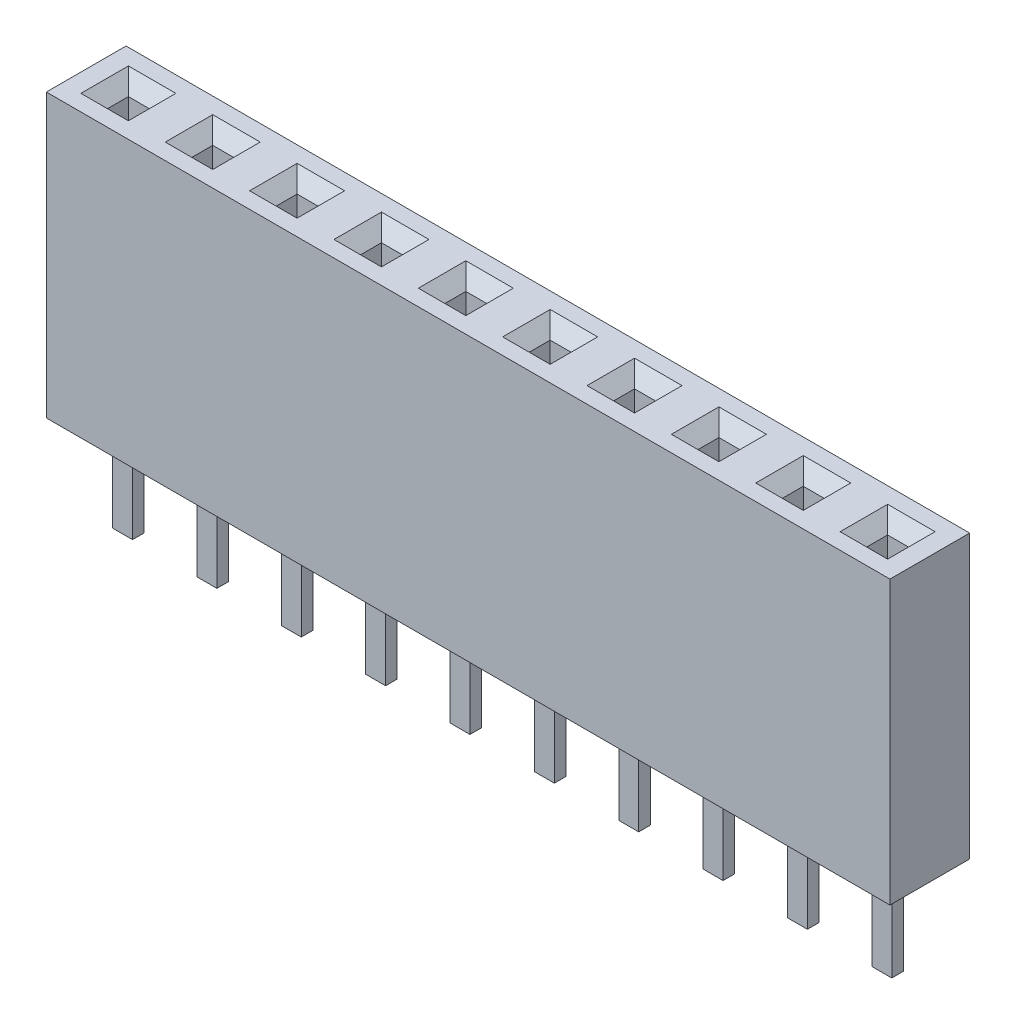
SolidWorks part; units mm, degrees
ref_plane "Front Plane" through (0, 0, 0) normal (0, 0, 1) x (1, 0, 0)
ref_plane "Top Plane" through (0, 0, 0) normal (0, 1, 0) x (1, 0, 0)
ref_plane "Right Plane" through (0, 0, 0) normal (1, 0, 0) x (0, 0, -1)
sketch "Sketch1" plane through (0, 0, 0) normal (0, 1, 0) x (1, 0, 0)
  line L1 (19.05, -1.2) -> (-19.05, -1.2)
  line L2 (19.05, -1.2) -> (19.05, 1.2)
  line L3 (19.05, 1.2) -> (-19.05, 1.2)
  line L4 (-19.05, -1.2) -> (-19.05, 1.2)
  line L5 (19.05, -1.2) -> (-19.05, 1.2) construction
  line L6 (19.05, 1.2) -> (-19.05, -1.2) construction
  point P0 (0, 0)
  dimension "D1" = 2.4
  dimension "D2" = 38.1
extrude "Boss-Extrude1" add sketch "Sketch1" along normal blind 8.5
sketch "Sketch2" plane through (0, 8.5, 0) normal (0, 1, 0) x (1, 0, 0)
  line L0 (-19.05, 0) -> (19.05, 0) construction
  line L1 (-19.05, 1.2) -> (-19.05, -1.2) construction
  line L2 (19.05, -1.2) -> (19.05, 1.2) construction
  line L3 (-15.555, 0.315) -> (-14.925, 0.315)
  line L4 (-18.095, -0.315) -> (-17.465, -0.315)
  line L5 (-18.095, -0.315) -> (-18.095, 0.315)
  line L6 (-18.095, 0.315) -> (-17.465, 0.315)
  line L7 (-17.465, -0.315) -> (-17.465, 0.315)
  line L8 (-18.095, -0.315) -> (-17.465, 0.315) construction
  line L9 (-18.095, 0.315) -> (-17.465, -0.315) construction
  line L10 (-15.555, -0.315) -> (-15.555, 0.315)
  line L11 (-15.555, -0.315) -> (-14.925, -0.315)
  line L12 (-14.925, -0.315) -> (-14.925, 0.315)
  line L13 (-13.015, 0.315) -> (-12.385, 0.315)
  line L14 (-13.015, -0.315) -> (-13.015, 0.315)
  line L15 (-13.015, -0.315) -> (-12.385, -0.315)
  line L16 (-12.385, -0.315) -> (-12.385, 0.315)
  line L17 (-10.475, 0.315) -> (-9.845, 0.315)
  line L18 (-10.475, -0.315) -> (-10.475, 0.315)
  line L19 (-10.475, -0.315) -> (-9.845, -0.315)
  line L20 (-9.845, -0.315) -> (-9.845, 0.315)
  line L21 (-7.935, 0.315) -> (-7.305, 0.315)
  line L22 (-7.935, -0.315) -> (-7.935, 0.315)
  line L23 (-7.935, -0.315) -> (-7.305, -0.315)
  line L24 (-7.305, -0.315) -> (-7.305, 0.315)
  line L25 (-5.395, 0.315) -> (-4.765, 0.315)
  line L26 (-5.395, -0.315) -> (-5.395, 0.315)
  line L27 (-5.395, -0.315) -> (-4.765, -0.315)
  line L28 (-4.765, -0.315) -> (-4.765, 0.315)
  line L29 (-2.855, 0.315) -> (-2.225, 0.315)
  line L30 (-2.855, -0.315) -> (-2.855, 0.315)
  line L31 (-2.855, -0.315) -> (-2.225, -0.315)
  line L32 (-2.225, -0.315) -> (-2.225, 0.315)
  line L33 (-0.315, 0.315) -> (0.315, 0.315)
  line L34 (-0.315, -0.315) -> (-0.315, 0.315)
  line L35 (-0.315, -0.315) -> (0.315, -0.315)
  line L36 (0.315, -0.315) -> (0.315, 0.315)
  line L37 (2.225, 0.315) -> (2.855, 0.315)
  line L38 (2.225, -0.315) -> (2.225, 0.315)
  line L39 (2.225, -0.315) -> (2.855, -0.315)
  line L40 (2.855, -0.315) -> (2.855, 0.315)
  line L41 (4.765, 0.315) -> (5.395, 0.315)
  line L42 (4.765, -0.315) -> (4.765, 0.315)
  line L43 (4.765, -0.315) -> (5.395, -0.315)
  line L44 (5.395, -0.315) -> (5.395, 0.315)
  line L45 (7.305, 0.315) -> (7.935, 0.315)
  line L46 (7.305, -0.315) -> (7.305, 0.315)
  line L47 (7.305, -0.315) -> (7.935, -0.315)
  line L48 (7.935, -0.315) -> (7.935, 0.315)
  line L49 (9.845, 0.315) -> (10.475, 0.315)
  line L50 (9.845, -0.315) -> (9.845, 0.315)
  line L51 (9.845, -0.315) -> (10.475, -0.315)
  line L52 (10.475, -0.315) -> (10.475, 0.315)
  line L53 (12.385, 0.315) -> (13.015, 0.315)
  line L54 (12.385, -0.315) -> (12.385, 0.315)
  line L55 (12.385, -0.315) -> (13.015, -0.315)
  line L56 (13.015, -0.315) -> (13.015, 0.315)
  line L57 (14.925, 0.315) -> (15.555, 0.315)
  line L58 (14.925, -0.315) -> (14.925, 0.315)
  line L59 (14.925, -0.315) -> (15.555, -0.315)
  line L60 (15.555, -0.315) -> (15.555, 0.315)
  line L61 (17.465, 0.315) -> (18.095, 0.315)
  line L62 (17.465, -0.315) -> (17.465, 0.315)
  line L63 (17.465, -0.315) -> (18.095, -0.315)
  line L64 (18.095, -0.315) -> (18.095, 0.315)
  point P6 (-17.78, 0)
  dimension "D1" = 0.63
  dimension "D2" = 0.63
  dimension "D3" = 1.27
  dimension "D4" = 15
extrude "Cut-Extrude1" cut sketch "Sketch2" against normal blind 6.5
sketch "Sketch3" plane through (0, 0, 0) normal (0, -1, 0) x (1, 0, 0)
  line L0 (-19.05, 0) -> (19.05, 0) construction
  line L1 (-19.05, -1.2) -> (-19.05, 1.2) construction
  line L2 (19.05, 1.2) -> (19.05, -1.2) construction
  line L3 (-15.54, 0.175) -> (-14.94, 0.175)
  line L4 (-18.08, -0.175) -> (-17.48, -0.175)
  line L5 (-18.08, -0.175) -> (-18.08, 0.175)
  line L6 (-18.08, 0.175) -> (-17.48, 0.175)
  line L7 (-17.48, -0.175) -> (-17.48, 0.175)
  line L8 (-18.08, -0.175) -> (-17.48, 0.175) construction
  line L9 (-18.08, 0.175) -> (-17.48, -0.175) construction
  line L10 (-15.54, -0.175) -> (-15.54, 0.175)
  line L11 (-15.54, -0.175) -> (-14.94, -0.175)
  line L12 (-14.94, -0.175) -> (-14.94, 0.175)
  line L13 (-13, 0.175) -> (-12.4, 0.175)
  line L14 (-13, -0.175) -> (-13, 0.175)
  line L15 (-13, -0.175) -> (-12.4, -0.175)
  line L16 (-12.4, -0.175) -> (-12.4, 0.175)
  line L17 (-10.46, 0.175) -> (-9.86, 0.175)
  line L18 (-10.46, -0.175) -> (-10.46, 0.175)
  line L19 (-10.46, -0.175) -> (-9.86, -0.175)
  line L20 (-9.86, -0.175) -> (-9.86, 0.175)
  line L21 (-7.92, 0.175) -> (-7.32, 0.175)
  line L22 (-7.92, -0.175) -> (-7.92, 0.175)
  line L23 (-7.92, -0.175) -> (-7.32, -0.175)
  line L24 (-7.32, -0.175) -> (-7.32, 0.175)
  line L25 (-5.38, 0.175) -> (-4.78, 0.175)
  line L26 (-5.38, -0.175) -> (-5.38, 0.175)
  line L27 (-5.38, -0.175) -> (-4.78, -0.175)
  line L28 (-4.78, -0.175) -> (-4.78, 0.175)
  line L29 (-2.84, 0.175) -> (-2.24, 0.175)
  line L30 (-2.84, -0.175) -> (-2.84, 0.175)
  line L31 (-2.84, -0.175) -> (-2.24, -0.175)
  line L32 (-2.24, -0.175) -> (-2.24, 0.175)
  line L33 (-0.3, 0.175) -> (0.3, 0.175)
  line L34 (-0.3, -0.175) -> (-0.3, 0.175)
  line L35 (-0.3, -0.175) -> (0.3, -0.175)
  line L36 (0.3, -0.175) -> (0.3, 0.175)
  line L37 (2.24, 0.175) -> (2.84, 0.175)
  line L38 (2.24, -0.175) -> (2.24, 0.175)
  line L39 (2.24, -0.175) -> (2.84, -0.175)
  line L40 (2.84, -0.175) -> (2.84, 0.175)
  line L41 (4.78, 0.175) -> (5.38, 0.175)
  line L42 (4.78, -0.175) -> (4.78, 0.175)
  line L43 (4.78, -0.175) -> (5.38, -0.175)
  line L44 (5.38, -0.175) -> (5.38, 0.175)
  line L45 (7.32, 0.175) -> (7.92, 0.175)
  line L46 (7.32, -0.175) -> (7.32, 0.175)
  line L47 (7.32, -0.175) -> (7.92, -0.175)
  line L48 (7.92, -0.175) -> (7.92, 0.175)
  line L49 (9.86, 0.175) -> (10.46, 0.175)
  line L50 (9.86, -0.175) -> (9.86, 0.175)
  line L51 (9.86, -0.175) -> (10.46, -0.175)
  line L52 (10.46, -0.175) -> (10.46, 0.175)
  line L53 (12.4, 0.175) -> (13, 0.175)
  line L54 (12.4, -0.175) -> (12.4, 0.175)
  line L55 (12.4, -0.175) -> (13, -0.175)
  line L56 (13, -0.175) -> (13, 0.175)
  line L57 (14.94, 0.175) -> (15.54, 0.175)
  line L58 (14.94, -0.175) -> (14.94, 0.175)
  line L59 (14.94, -0.175) -> (15.54, -0.175)
  line L60 (15.54, -0.175) -> (15.54, 0.175)
  line L61 (17.48, 0.175) -> (18.08, 0.175)
  line L62 (17.48, -0.175) -> (17.48, 0.175)
  line L63 (17.48, -0.175) -> (18.08, -0.175)
  line L64 (18.08, -0.175) -> (18.08, 0.175)
  point P6 (-17.78, 0)
  dimension "D1" = 0.35
  dimension "D2" = 0.6
  dimension "D3" = 1.27
  dimension "D4" = 15
extrude "Boss-Extrude2" add sketch "Sketch3" along normal blind 2.9
chamfer "Chamfer1" distance 0.4 angle 45 60 edges at (0, 8.5, 0.315) (0.315, 8.5, 0) (0, 8.5, -0.315) (-0.315, 8.5, 0) (-2.54, 8.5, 0.315) (-2.225, 8.5, 0) (-2.54, 8.5, -0.315) (-2.855, 8.5, 0) (-5.08, 8.5, 0.315) (-4.765, 8.5, 0) (-5.08, 8.5, -0.315) (-5.395, 8.5, 0) (-7.62, 8.5, 0.315) (-7.305, 8.5, 0) (-7.62, 8.5, -0.315) (-7.935, 8.5, 0) (-10.16, 8.5, 0.315) (-9.845, 8.5, 0) (-10.16, 8.5, -0.315) (-10.475, 8.5, 0) (-12.385, 8.5, 0) (-12.7, 8.5, -0.315) (-13.015, 8.5, 0) (-12.7, 8.5, 0.315) (-15.24, 8.5, 0.315) (-14.925, 8.5, 0) (-15.24, 8.5, -0.315) (-15.555, 8.5, 0) (-17.78, 8.5, 0.315) (-17.465, 8.5, 0) (-17.78, 8.5, -0.315) (-18.095, 8.5, 0) (17.78, 8.5, 0.315) (18.095, 8.5, 0) (17.78, 8.5, -0.315) (17.465, 8.5, 0) (15.24, 8.5, 0.315) (15.555, 8.5, 0) (15.24, 8.5, -0.315) (14.925, 8.5, 0) (12.385, 8.5, 0) (12.7, 8.5, 0.315) (13.015, 8.5, 0) (12.7, 8.5, -0.315) (9.845, 8.5, 0) (10.16, 8.5, 0.315) (10.475, 8.5, 0) (10.16, 8.5, -0.315) (7.305, 8.5, 0) (7.62, 8.5, 0.315) (7.935, 8.5, 0) (7.62, 8.5, -0.315) (4.765, 8.5, 0) (5.08, 8.5, 0.315) (5.395, 8.5, 0) (5.08, 8.5, -0.315) (2.225, 8.5, 0) (2.54, 8.5, -0.315) (2.855, 8.5, 0) (2.54, 8.5, 0.315)
sketch "Sketch4" plane through (0, 8.5, 0) normal (0, 1, 0) x (1, 0, 0)
  line L0 (5.395, 0) -> (7.305, 0) construction
  line L3 (6.35, 0) -> (6.35, 2.1388) construction
  line L4 (5.395, -0.315) -> (5.395, 0.315) construction
  line L5 (6.35, 2.1388) -> (25.7288, 2.1388)
  line L6 (6.35, 2.1388) -> (6.35, -2.3327)
  line L7 (6.35, -2.3327) -> (25.7288, -2.3327)
  line L8 (25.7288, 2.1388) -> (25.7288, -2.3327)
  line L9 (7.305, 0.315) -> (7.305, -0.315) construction
  point P11 (6.35, 0)
extrude "Cut-Extrude2" cut sketch "Sketch4" against normal through all
sketch "Sketch5" plane through (0, 0, 0) normal (0, -1, 0) x (-1, 0, 0)
  line L0 (17.78, -1.2) -> (17.78, 1.2) construction
  line L1 (19.05, -1.2) -> (-6.35, -1.2) construction
  line L2 (-6.35, 1.2) -> (19.05, 1.2) construction
  line L3 (18.08, 0) -> (17.48, 0) construction
  line L4 (18.08, -0.175) -> (18.08, 0.175) construction
  line L5 (17.48, 0.175) -> (17.48, -0.175) construction
  point P12 (17.78, 0)
sketch "Sketch6" plane through (0, 8.5, 0) normal (0, 1, 0) x (1, 0, 0)
  line L0 (-18.495, 0) -> (-17.065, 0) construction
  line L1 (-18.495, -0.715) -> (-18.495, 0.715) construction
  line L2 (-17.065, 0.715) -> (-17.065, -0.715) construction
  line L3 (4.365, 0) -> (5.795, 0) construction
  line L4 (4.365, -0.715) -> (4.365, 0.715) construction
  line L5 (5.795, 0.715) -> (5.795, -0.715) construction
  point P12 (-17.78, 0)
  point P13 (5.08, 0)
